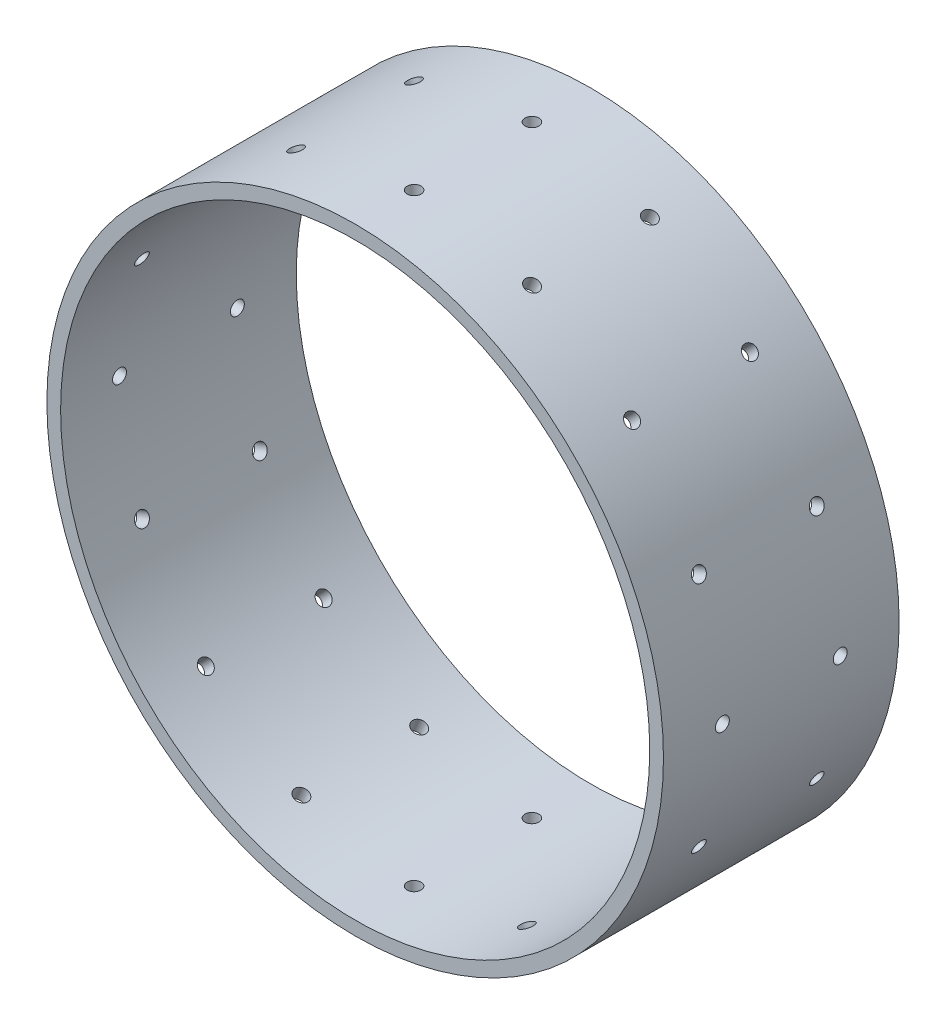
SolidWorks part; units mm, degrees
ref_plane "Front Plane" through (0, 0, 0) normal (0, 0, 1) x (1, 0, 0)
ref_plane "Top Plane" through (0, 0, 0) normal (0, 1, 0) x (1, 0, 0)
ref_plane "Right Plane" through (0, 0, 0) normal (1, 0, 0) x (0, 0, -1)
sketch "Sketch1" plane through (0, 0, 0) normal (0, 0, 1) x (1, 0, 0)
  circle A0 centre (0, 0) radius 63.5
  circle A1 centre (0, 0) radius 66.4591
  dimension "D1" = 127
  dimension "D2" = 132.9182
extrude "Extrude1" add sketch "Sketch1" along normal blind 50.8
ref_plane "Plane1" through (0, 0, 12.7) normal (0, 0, -1) x (-1, 0, 0)
sketch "Sketch2" plane through (0, 0, 12.7) normal (0, 0, -1) x (-1, 0, 0)
  line L0 (0, 0) -> (0, 66.4591) construction
  line L1 (0, 0) -> (12.9655, 65.1821) construction
  circle A0 centre (0, 0) radius 66.4591 construction
  dimension "D1" = 11.25
ref_plane "Plane4" through (0, 66.4591, 12.7) normal (0, 1, 0) x (-1, 0, 0)
sketch "Sketch7" plane through (0, 66.4591, 12.7) normal (0, 1, 0) x (-1, 0, 0)
  line L0 (0, 0) -> (0, 25.4) construction
hole_wizard "M3x0.5 Tapped Hole1" positions "Sketch9" profile "Sketch8" tap size "M3x0.5" standard "ANSI Metric"
sketch "Sketch9" plane through (0, 66.4591, 12.7) normal (0, 1, 0) x (-1, 0, 0)
  point P1 (0, 0)
  point P4 (0, 25.4)
sketch "Sketch8" plane through (0, 66.4591, 12.7) normal (1, 0, 0) x (0, 0, 1)
  line L0 (0, 0) -> (0, 8.3711)
  line L1 (0, 8.3711) -> (1.25, 7.62)
  line L2 (1.25, 7.62) -> (1.25, 6.096)
  line L3 (1.25, 6.096) -> (1.5, 6.096)
  line L4 (1.5, 6.096) -> (1.5, 0)
  line L5 (1.5, 0) -> (0, 0)
  line L10 (0, 8.3711) -> (-1.25, 7.62) construction
  line L11 (0, -6.35) -> (0, 107.95) construction
  dimension "Tap Drill Dia." = 2.5
  dimension "Tap Drill Depth" = 7.62
  dimension "Thread Major Dia." = 3
  dimension "Thread Depth" = 6.096
  dimension "Drill Angle" = 118
pattern_circular "CirPattern1" count 16 over 360 about axis through (0, 0, 50.8) along (0, 0, -1) of "M3x0.5 Tapped Hole1"
ref_plane "Plane5" through (-12.9655, 65.1821, 12.7) normal (-0.1951, 0.9808, 0) x (-0.9808, -0.1951, 0)
hole_wizard "3/8 Clearance Hole1" [suppressed] positions "Sketch13" profile "Sketch14" hole size "3/8" standard "Ansi Inch"
sketch "Sketch13" plane through (-13.0076, 65.3939, 12.7) normal (-0.1951, 0.9808, 0) x (-0.9808, -0.1951, 0)
  point P1 (0, 0)
sketch "Sketch14" plane through (-13.0076, 65.3939, 12.7) normal (0, 0, 1) x (-0.9808, -0.1951, 0)
  line L0 (0, 0) -> (0, 15.9835)
  line L1 (0, 15.9835) -> (5.0419, 12.954)
  line L2 (5.0419, 12.954) -> (5.0419, 3.175)
  line L3 (5.0419, 3.175) -> (8.2169, 0)
  line L5 (8.2169, 0) -> (0, 0)
  line L6 (-5.0419, 3.175) -> (-8.2169, 0) construction
  line L10 (0, 15.9835) -> (-5.0419, 12.954) construction
  line L11 (0, -6.35) -> (0, 107.95) construction
  dimension "Hole Dia." = 10.0838
  dimension "Hole Depth" = 12.954
  dimension "Near C'Sink Dia." = 16.4338
  dimension "Near C'Sink Angle" = 90
  dimension "Drill Angle" = 118
ref_plane "Plane6" through (0, 0, 12.7) normal (-0.1951, 0.9808, 0) x (-0.9808, -0.1951, 0)
mirror "Mirror1" [suppressed] about plane through (0, 0, 12.7) normal (-0.1951, 0.9808, 0)
